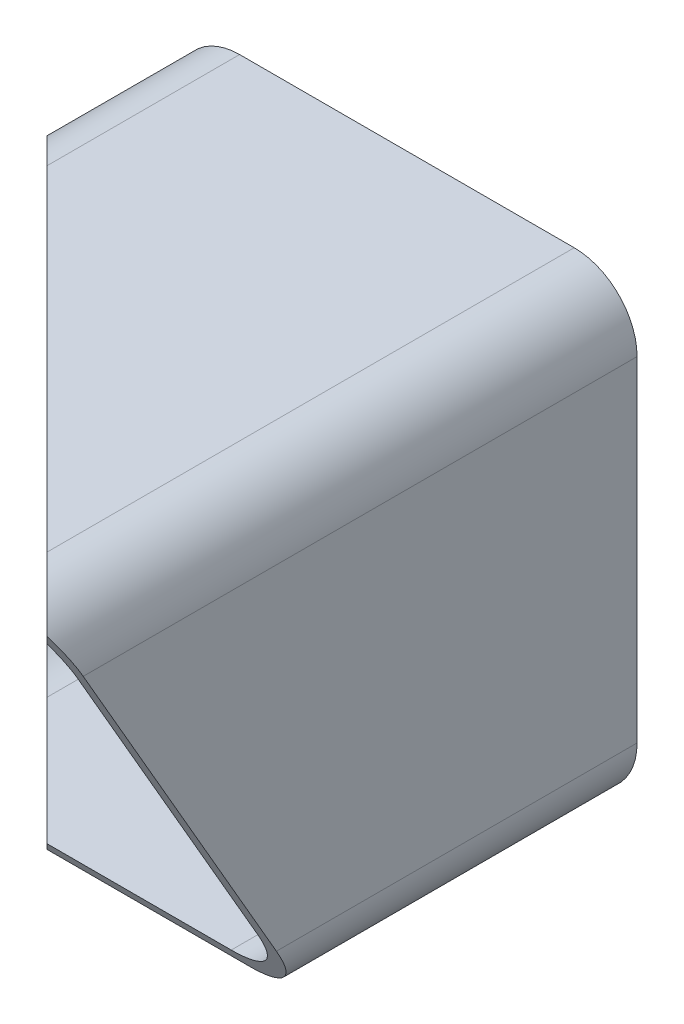
SolidWorks part; units mm, degrees
ref_plane "Front Plane" through (0, 0, 0) normal (0, 0, 1) x (1, 0, 0)
ref_plane "Top Plane" through (0, 0, 0) normal (0, 1, 0) x (1, 0, 0)
ref_plane "Right Plane" through (0, 0, 0) normal (1, 0, 0) x (0, 0, -1)
sketch "Sketch1" plane through (0, 0, 0) normal (0, 0, 1) x (1, 0, 0)
  line L1 (-37, -37) -> (37, -37)
  line L2 (-37, -37) -> (-37, 37)
  line L3 (-37, 37) -> (37, 37)
  line L4 (37, -37) -> (37, 37)
  line L5 (-37, -37) -> (37, 37) construction
  line L6 (-37, 37) -> (37, -37) construction
  line L7 (-39, -39) -> (39, -39)
  line L8 (-39, -39) -> (-39, 39)
  line L9 (-39, 39) -> (39, 39)
  line L10 (39, -39) -> (39, 39)
  line L11 (-39, -39) -> (39, 39) construction
  line L12 (-39, 39) -> (39, -39) construction
  point P0 (0, 0)
  point P6 (0, 0)
  point P11 (0, 0)
  dimension "D1" = 74
  dimension "D2" = 2
extrude "Boss-Extrude1" add sketch "Sketch1" along normal mid plane 100
fillet "Fillet1" radius 10.65 8 edges at (37, -37, 0) (37, 37, 0) (-39, -39, 0) (-37, -37, 0) (39, -39, 0) (39, 39, 0) (-37, 37, 0) (-39, 39, 0)
sketch "Sketch2" plane through (39, 0, 0) normal (1, 0, 0) x (0, 0, -1)
  line L0 (-50, 39) -> (-50, -39)
  line L1 (-50, -39) -> (-4.9667, -39)
  line L2 (50, -39) -> (-50, -39) construction
  line L3 (-4.9667, -39) -> (-50, 39)
  dimension "D1" = 30
extrude "Cut-Extrude1" cut sketch "Sketch2" against normal through all
sketch "Sketch3" plane through (0, 39, 0) normal (0, 1, 0) x (1, 0, 0)
  line L0 (-39, -50) -> (39, -50)
  line L1 (39, -50) -> (-39, 28)
  line L2 (-39, -43.8512) -> (-39, 50) construction
  line L3 (-39, 28) -> (-39, -50)
  line L4 (28.35, -50) -> (-28.35, -50) construction
  line L5 (39, 50) -> (39, -43.8512) construction
  point P7 (0, 0)
  dimension "D1" = 45
extrude "Cut-Extrude2" cut sketch "Sketch3" against normal through all
